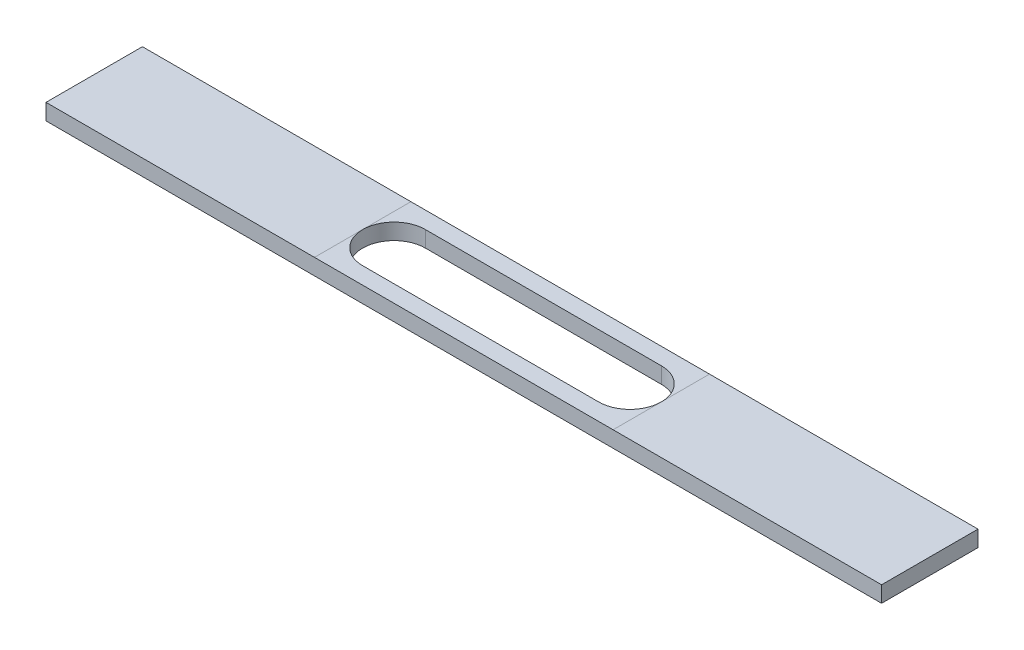
SolidWorks part; units mm, degrees
material "Acrylic (Medium-high impact)"
ref_plane "Front Plane" through (0, 0, 0) normal (0, 0, 1) x (1, 0, 0)
ref_plane "Top Plane" through (0, 0, 0) normal (0, 1, 0) x (1, 0, 0)
ref_plane "Right Plane" through (0, 0, 0) normal (1, 0, 0) x (0, 0, -1)
sketch "Sketch1" plane through (0, 0, 0) normal (0, 1, 0) x (1, 0, 0)
  line L1 (82.55, -9.525) -> (-82.55, -9.525)
  line L2 (82.55, -9.525) -> (82.55, 9.525)
  line L3 (82.55, 9.525) -> (-82.55, 9.525)
  line L4 (-82.55, -9.525) -> (-82.55, 9.525)
  line L5 (82.55, -9.525) -> (-82.55, 9.525) construction
  line L6 (82.55, 9.525) -> (-82.55, -9.525) construction
  point P0 (0, 0)
  dimension "D1" = 19.05
  dimension "D2" = 165.1
extrude "Boss-Extrude1" add sketch "Sketch1" along normal blind 3.175 contours L3 L4 L1 L2
sketch "Sketch3" plane through (0, 3.175, 0) normal (0, 1, 0) x (1, 0, 0)
  line L0 (-29.5, 9.525) -> (-29.5, -9.525)
  line L1 (82.55, 9.525) -> (-82.55, 9.525) construction
  line L2 (82.55, -9.525) -> (-82.55, -9.525) construction
  line L3 (29.5, 9.525) -> (29.5, -9.525)
  line L4 (29.5, 0) -> (-29.5, 0) construction
  point P12 (0, 0)
  dimension "D1" = 59
split line "Split Line1"
sketch "Sketch4" plane through (0, 3.175, 0) normal (0, 1, 0) x (1, 0, 0)
  line L0 (-29.5, -9.525) -> (-29.5, 9.525) construction
  ellipse E0 centre (0, 0) end of major axis (-29.5, 0) minor radius 6.0325
  dimension "D1" = 12.065
extrude "Ellipse" [suppressed] cut sketch "Sketch4" against normal through all
sketch "Sketch5" plane through (0, 3.175, 0) normal (0, 1, 0) x (1, 0, 0)
  line L0 (-23.31, 0) -> (23.31, 0) construction
  line L4 (-23.31, 6.19) -> (23.31, 6.19)
  line L5 (-23.31, -6.19) -> (23.31, -6.19)
  line L6 (29.5, -9.525) -> (29.5, 9.525) construction
  arc A2 (-23.31, 6.19) -> (-23.31, -6.19) centre (-23.31, 0) ccw
  arc A3 (23.31, -6.19) -> (23.31, 6.19) centre (23.31, 0) ccw
  point P2 (0, 0)
  dimension "D1" = 12.38
extrude "Slot" cut sketch "Sketch5" against normal through all
sketch "Sketch6" [suppressed] plane through (0, 3.175, 0) normal (0, 1, 0) x (1, 0, 0)
  line L0 (-24.2316, 7.1289) -> (-19.1516, 7.1289) construction
  line L1 (-24.2316, 8.2973) -> (-19.1516, 8.2973)
  line L2 (-24.2316, 5.9605) -> (-19.1516, 5.9605)
  line L3 (-15.555, 7.1289) -> (-10.475, 7.1289) construction
  line L4 (-15.555, 8.2973) -> (-10.475, 8.2973)
  line L5 (-15.555, 5.9605) -> (-10.475, 5.9605)
  line L6 (-6.8783, 7.1289) -> (-1.7983, 7.1289) construction
  line L7 (-6.8783, 8.2973) -> (-1.7983, 8.2973)
  line L8 (-6.8783, 5.9605) -> (-1.7983, 5.9605)
  line L9 (1.7983, 7.1289) -> (6.8783, 7.1289) construction
  line L10 (1.7983, 8.2973) -> (6.8783, 8.2973)
  line L11 (1.7983, 5.9605) -> (6.8783, 5.9605)
  line L12 (10.475, 7.1289) -> (15.555, 7.1289) construction
  line L13 (10.475, 8.2973) -> (15.555, 8.2973)
  line L14 (10.475, 5.9605) -> (15.555, 5.9605)
  line L15 (19.1516, 7.1289) -> (24.2316, 7.1289) construction
  line L16 (19.1516, 8.2973) -> (24.2316, 8.2973)
  line L17 (19.1516, 5.9605) -> (24.2316, 5.9605)
  line L18 (-15.555, 3.5645) -> (-10.475, 3.5645) construction
  line L19 (-15.555, 4.7329) -> (-10.475, 4.7329)
  line L20 (-15.555, 2.3961) -> (-10.475, 2.3961)
  line L21 (-6.8783, 3.5645) -> (-1.7983, 3.5645) construction
  line L22 (-6.8783, 4.7329) -> (-1.7983, 4.7329)
  line L23 (-6.8783, 2.3961) -> (-1.7983, 2.3961)
  line L24 (1.7983, 3.5645) -> (6.8783, 3.5645) construction
  line L25 (1.7983, 4.7329) -> (6.8783, 4.7329)
  line L26 (1.7983, 2.3961) -> (6.8783, 2.3961)
  line L27 (10.475, 3.5645) -> (15.555, 3.5645) construction
  line L28 (10.475, 4.7329) -> (15.555, 4.7329)
  line L29 (10.475, 2.3961) -> (15.555, 2.3961)
  line L30 (19.1516, 3.5645) -> (24.2316, 3.5645) construction
  line L31 (19.1516, 4.7329) -> (24.2316, 4.7329)
  line L32 (19.1516, 2.3961) -> (24.2316, 2.3961)
  line L33 (-15.555, 0) -> (-10.475, 0) construction
  line L34 (-15.555, 1.1684) -> (-10.475, 1.1684)
  line L35 (-15.555, -1.1684) -> (-10.475, -1.1684)
  line L36 (-6.8783, 0) -> (-1.7983, 0) construction
  line L37 (-6.8783, 1.1684) -> (-1.7983, 1.1684)
  line L38 (-6.8783, -1.1684) -> (-1.7983, -1.1684)
  line L39 (1.7983, 0) -> (6.8783, 0) construction
  line L40 (1.7983, 1.1684) -> (6.8783, 1.1684)
  line L41 (1.7983, -1.1684) -> (6.8783, -1.1684)
  line L42 (10.475, 0) -> (15.555, 0) construction
  line L43 (10.475, 1.1684) -> (15.555, 1.1684)
  line L44 (10.475, -1.1684) -> (15.555, -1.1684)
  line L45 (19.1516, 0) -> (24.2316, 0) construction
  line L46 (19.1516, 1.1684) -> (24.2316, 1.1684)
  line L47 (19.1516, -1.1684) -> (24.2316, -1.1684)
  line L48 (-15.555, -3.5645) -> (-10.475, -3.5645) construction
  line L49 (-15.555, -2.3961) -> (-10.475, -2.3961)
  line L50 (-15.555, -4.7329) -> (-10.475, -4.7329)
  line L51 (-6.8783, -3.5645) -> (-1.7983, -3.5645) construction
  line L52 (-6.8783, -2.3961) -> (-1.7983, -2.3961)
  line L53 (-6.8783, -4.7329) -> (-1.7983, -4.7329)
  line L54 (1.7983, -3.5645) -> (6.8783, -3.5645) construction
  line L55 (1.7983, -2.3961) -> (6.8783, -2.3961)
  line L56 (1.7983, -4.7329) -> (6.8783, -4.7329)
  line L57 (10.475, -3.5645) -> (15.555, -3.5645) construction
  line L58 (10.475, -2.3961) -> (15.555, -2.3961)
  line L59 (10.475, -4.7329) -> (15.555, -4.7329)
  line L60 (19.1516, -3.5645) -> (24.2316, -3.5645) construction
  line L61 (19.1516, -2.3961) -> (24.2316, -2.3961)
  line L62 (19.1516, -4.7329) -> (24.2316, -4.7329)
  line L63 (-15.555, -7.1289) -> (-10.475, -7.1289) construction
  line L64 (-15.555, -5.9605) -> (-10.475, -5.9605)
  line L65 (-15.555, -8.2973) -> (-10.475, -8.2973)
  line L66 (-6.8783, -7.1289) -> (-1.7983, -7.1289) construction
  line L67 (-6.8783, -5.9605) -> (-1.7983, -5.9605)
  line L68 (-6.8783, -8.2973) -> (-1.7983, -8.2973)
  line L69 (1.7983, -7.1289) -> (6.8783, -7.1289) construction
  line L70 (1.7983, -5.9605) -> (6.8783, -5.9605)
  line L71 (1.7983, -8.2973) -> (6.8783, -8.2973)
  line L72 (10.475, -7.1289) -> (15.555, -7.1289) construction
  line L73 (10.475, -5.9605) -> (15.555, -5.9605)
  line L74 (10.475, -8.2973) -> (15.555, -8.2973)
  line L75 (19.1516, -7.1289) -> (24.2316, -7.1289) construction
  line L76 (19.1516, -5.9605) -> (24.2316, -5.9605)
  line L77 (19.1516, -8.2973) -> (24.2316, -8.2973)
  line L78 (-24.2316, 3.5645) -> (-19.1516, 3.5645) construction
  line L79 (-24.2316, 4.7329) -> (-19.1516, 4.7329)
  line L80 (-24.2316, 2.3961) -> (-19.1516, 2.3961)
  line L81 (-24.2316, 0) -> (-19.1516, 0) construction
  line L82 (-24.2316, 1.1684) -> (-19.1516, 1.1684)
  line L83 (-24.2316, -1.1684) -> (-19.1516, -1.1684)
  line L84 (-24.2316, -3.5645) -> (-19.1516, -3.5645) construction
  line L85 (-24.2316, -2.3961) -> (-19.1516, -2.3961)
  line L86 (-24.2316, -4.7329) -> (-19.1516, -4.7329)
  line L87 (-24.2316, -7.1289) -> (-19.1516, -7.1289) construction
  line L88 (-24.2316, -5.9605) -> (-19.1516, -5.9605)
  line L89 (-24.2316, -8.2973) -> (-19.1516, -8.2973)
  line L90 (-25.4, -9.525) -> (-25.4, 9.525) construction
  line L92 (25.4, -9.525) -> (25.4, 9.525) construction
  line L93 (-24.2316, 8.2973) -> (-24.2316, 9.525) construction
  line L94 (25.4, 9.525) -> (-25.4, 9.525) construction
  line L95 (-24.2316, -8.2973) -> (-24.2316, -9.525) construction
  line L96 (25.4, -9.525) -> (-25.4, -9.525) construction
  line L97 (-24.2316, -5.9605) -> (-24.2316, -4.7329) construction
  arc A0 (-24.2316, 8.2973) -> (-24.2316, 5.9605) centre (-24.2316, 7.1289) ccw
  arc A1 (-19.1516, 5.9605) -> (-19.1516, 8.2973) centre (-19.1516, 7.1289) ccw
  arc A2 (-15.555, 8.2973) -> (-15.555, 5.9605) centre (-15.555, 7.1289) ccw
  arc A3 (-10.475, 5.9605) -> (-10.475, 8.2973) centre (-10.475, 7.1289) ccw
  arc A4 (-6.8783, 8.2973) -> (-6.8783, 5.9605) centre (-6.8783, 7.1289) ccw
  arc A5 (-1.7983, 5.9605) -> (-1.7983, 8.2973) centre (-1.7983, 7.1289) ccw
  arc A6 (1.7983, 8.2973) -> (1.7983, 5.9605) centre (1.7983, 7.1289) ccw
  arc A7 (6.8783, 5.9605) -> (6.8783, 8.2973) centre (6.8783, 7.1289) ccw
  arc A8 (10.475, 8.2973) -> (10.475, 5.9605) centre (10.475, 7.1289) ccw
  arc A9 (15.555, 5.9605) -> (15.555, 8.2973) centre (15.555, 7.1289) ccw
  arc A10 (19.1516, 8.2973) -> (19.1516, 5.9605) centre (19.1516, 7.1289) ccw
  arc A11 (24.2316, 5.9605) -> (24.2316, 8.2973) centre (24.2316, 7.1289) ccw
  arc A12 (-15.555, 4.7329) -> (-15.555, 2.3961) centre (-15.555, 3.5645) ccw
  arc A13 (-10.475, 2.3961) -> (-10.475, 4.7329) centre (-10.475, 3.5645) ccw
  arc A14 (-6.8783, 4.7329) -> (-6.8783, 2.3961) centre (-6.8783, 3.5645) ccw
  arc A15 (-1.7983, 2.3961) -> (-1.7983, 4.7329) centre (-1.7983, 3.5645) ccw
  arc A16 (1.7983, 4.7329) -> (1.7983, 2.3961) centre (1.7983, 3.5645) ccw
  arc A17 (6.8783, 2.3961) -> (6.8783, 4.7329) centre (6.8783, 3.5645) ccw
  arc A18 (10.475, 4.7329) -> (10.475, 2.3961) centre (10.475, 3.5645) ccw
  arc A19 (15.555, 2.3961) -> (15.555, 4.7329) centre (15.555, 3.5645) ccw
  arc A20 (19.1516, 4.7329) -> (19.1516, 2.3961) centre (19.1516, 3.5645) ccw
  arc A21 (24.2316, 2.3961) -> (24.2316, 4.7329) centre (24.2316, 3.5645) ccw
  arc A22 (-15.555, 1.1684) -> (-15.555, -1.1684) centre (-15.555, 0) ccw
  arc A23 (-10.475, -1.1684) -> (-10.475, 1.1684) centre (-10.475, 0) ccw
  arc A24 (-6.8783, 1.1684) -> (-6.8783, -1.1684) centre (-6.8783, 0) ccw
  arc A25 (-1.7983, -1.1684) -> (-1.7983, 1.1684) centre (-1.7983, 0) ccw
  arc A26 (1.7983, 1.1684) -> (1.7983, -1.1684) centre (1.7983, 0) ccw
  arc A27 (6.8783, -1.1684) -> (6.8783, 1.1684) centre (6.8783, 0) ccw
  arc A28 (10.475, 1.1684) -> (10.475, -1.1684) centre (10.475, 0) ccw
  arc A29 (15.555, -1.1684) -> (15.555, 1.1684) centre (15.555, 0) ccw
  arc A30 (19.1516, 1.1684) -> (19.1516, -1.1684) centre (19.1516, 0) ccw
  arc A31 (24.2316, -1.1684) -> (24.2316, 1.1684) centre (24.2316, 0) ccw
  arc A32 (-15.555, -2.3961) -> (-15.555, -4.7329) centre (-15.555, -3.5645) ccw
  arc A33 (-10.475, -4.7329) -> (-10.475, -2.3961) centre (-10.475, -3.5645) ccw
  arc A34 (-6.8783, -2.3961) -> (-6.8783, -4.7329) centre (-6.8783, -3.5645) ccw
  arc A35 (-1.7983, -4.7329) -> (-1.7983, -2.3961) centre (-1.7983, -3.5645) ccw
  arc A36 (1.7983, -2.3961) -> (1.7983, -4.7329) centre (1.7983, -3.5645) ccw
  arc A37 (6.8783, -4.7329) -> (6.8783, -2.3961) centre (6.8783, -3.5645) ccw
  arc A38 (10.475, -2.3961) -> (10.475, -4.7329) centre (10.475, -3.5645) ccw
  arc A39 (15.555, -4.7329) -> (15.555, -2.3961) centre (15.555, -3.5645) ccw
  arc A40 (19.1516, -2.3961) -> (19.1516, -4.7329) centre (19.1516, -3.5645) ccw
  arc A41 (24.2316, -4.7329) -> (24.2316, -2.3961) centre (24.2316, -3.5645) ccw
  arc A42 (-15.555, -5.9605) -> (-15.555, -8.2973) centre (-15.555, -7.1289) ccw
  arc A43 (-10.475, -8.2973) -> (-10.475, -5.9605) centre (-10.475, -7.1289) ccw
  arc A44 (-6.8783, -5.9605) -> (-6.8783, -8.2973) centre (-6.8783, -7.1289) ccw
  arc A45 (-1.7983, -8.2973) -> (-1.7983, -5.9605) centre (-1.7983, -7.1289) ccw
  arc A46 (1.7983, -5.9605) -> (1.7983, -8.2973) centre (1.7983, -7.1289) ccw
  arc A47 (6.8783, -8.2973) -> (6.8783, -5.9605) centre (6.8783, -7.1289) ccw
  arc A48 (10.475, -5.9605) -> (10.475, -8.2973) centre (10.475, -7.1289) ccw
  arc A49 (15.555, -8.2973) -> (15.555, -5.9605) centre (15.555, -7.1289) ccw
  arc A50 (19.1516, -5.9605) -> (19.1516, -8.2973) centre (19.1516, -7.1289) ccw
  arc A51 (24.2316, -8.2973) -> (24.2316, -5.9605) centre (24.2316, -7.1289) ccw
  arc A52 (-24.2316, 4.7329) -> (-24.2316, 2.3961) centre (-24.2316, 3.5645) ccw
  arc A53 (-19.1516, 2.3961) -> (-19.1516, 4.7329) centre (-19.1516, 3.5645) ccw
  arc A54 (-24.2316, 1.1684) -> (-24.2316, -1.1684) centre (-24.2316, 0) ccw
  arc A55 (-19.1516, -1.1684) -> (-19.1516, 1.1684) centre (-19.1516, 0) ccw
  arc A56 (-24.2316, -2.3961) -> (-24.2316, -4.7329) centre (-24.2316, -3.5645) ccw
  arc A57 (-19.1516, -4.7329) -> (-19.1516, -2.3961) centre (-19.1516, -3.5645) ccw
  arc A58 (-24.2316, -5.9605) -> (-24.2316, -8.2973) centre (-24.2316, -7.1289) ccw
  arc A59 (-19.1516, -8.2973) -> (-19.1516, -5.9605) centre (-19.1516, -7.1289) ccw
  point P2 (-21.6916, 7.1289)
  point P11 (-13.015, 7.1289)
  point P18 (-4.3383, 7.1289)
  point P25 (4.3383, 7.1289)
  point P32 (13.015, 7.1289)
  point P39 (21.6916, 7.1289)
  point P46 (-13.015, 3.5645)
  point P53 (-4.3383, 3.5645)
  point P60 (4.3383, 3.5645)
  point P67 (13.015, 3.5645)
  point P74 (21.6916, 3.5645)
  point P81 (-13.015, 0)
  point P88 (-4.3383, 0)
  point P95 (4.3383, 0)
  point P102 (13.015, 0)
  point P109 (21.6916, 0)
  point P116 (-13.015, -3.5645)
  point P123 (-4.3383, -3.5645)
  point P130 (4.3383, -3.5645)
  point P137 (13.015, -3.5645)
  point P144 (21.6916, -3.5645)
  point P151 (-13.015, -7.1289)
  point P158 (-4.3383, -7.1289)
  point P165 (4.3383, -7.1289)
  point P172 (13.015, -7.1289)
  point P179 (21.6916, -7.1289)
  point P186 (-21.6916, 3.5645)
  point P193 (-21.6916, 0)
  point P200 (-21.6916, -3.5645)
  point P207 (-21.6916, -7.1289)
  point P217 (-25.4, 0)
  dimension "D4" = 1.1684
  dimension "D3" = 5.08
  dimension "D1" = 6
  dimension "D2" = 5
extrude "Slots" [suppressed] cut sketch "Sketch6" against normal through all
sketch "Sketch7" [suppressed] plane through (0, 3.175, 0) normal (0, 1, 0) x (1, 0, 0)
  line L1 (25.4, 9.525) -> (-25.4, 9.525) construction
  line L8 (7.366, 0) -> (0, 7.366)
  line L9 (7.366, 0) -> (0, -7.366)
  line L10 (0, 7.366) -> (-7.366, 0)
  line L11 (0, -7.366) -> (-7.366, 0)
  line L12 (7.366, 0) -> (-7.366, 0) construction
  line L13 (0, 7.366) -> (0, -7.366) construction
  line L14 (-10.668, 0) -> (-18.034, 7.366)
  line L15 (-10.668, 0) -> (-18.034, -7.366)
  line L16 (-18.034, 7.366) -> (-25.4, 0)
  line L17 (-18.034, -7.366) -> (-25.4, 0)
  line L18 (-10.668, 0) -> (-25.4, 0) construction
  line L19 (-18.034, 7.366) -> (-18.034, -7.366) construction
  line L20 (-25.4, -9.525) -> (-25.4, 9.525) construction
  line L21 (-14.9807, 7.366) -> (-9.017, 1.4023)
  line L22 (-25.4, 3.0533) -> (-25.4, 7.366)
  line L23 (-10.668, 0) -> (-7.366, 0) construction
  line L24 (-9.017, 1.4023) -> (-3.0533, 7.366)
  line L25 (-3.0533, 7.366) -> (-14.9807, 7.366)
  line L26 (-10.668, 0) -> (-9.017, 1.4023) construction
  line L27 (-7.366, 0) -> (-9.017, 1.4023) construction
  line L28 (-25.4, 3.0533) -> (-21.0873, 7.366)
  line L29 (-21.0873, 7.366) -> (-25.4, 7.366)
  line L30 (-21.0873, 7.366) -> (-18.034, 7.366) construction
  line L31 (-14.9807, 7.366) -> (-18.034, 7.366) construction
  line L32 (-3.0533, -7.366) -> (-14.9807, -7.366)
  line L33 (-9.017, -1.4023) -> (-3.0533, -7.366)
  line L34 (-14.9807, -7.366) -> (-9.017, -1.4023)
  line L35 (-25.4, -3.0533) -> (-25.4, -7.366)
  line L36 (-21.0873, -7.366) -> (-25.4, -7.366)
  line L37 (-25.4, -3.0533) -> (-21.0873, -7.366)
  line L38 (14.9807, 7.366) -> (18.034, 7.366) construction
  line L39 (21.0873, 7.366) -> (18.034, 7.366) construction
  line L40 (7.366, 0) -> (9.017, 1.4023) construction
  line L41 (10.668, 0) -> (9.017, 1.4023) construction
  line L42 (10.668, 0) -> (7.366, 0) construction
  line L43 (18.034, 7.366) -> (18.034, -7.366) construction
  line L44 (10.668, 0) -> (25.4, 0) construction
  line L45 (25.4, -3.0533) -> (21.0873, -7.366)
  line L46 (21.0873, -7.366) -> (25.4, -7.366)
  line L47 (25.4, -3.0533) -> (25.4, -7.366)
  line L48 (14.9807, -7.366) -> (9.017, -1.4023)
  line L49 (9.017, -1.4023) -> (3.0533, -7.366)
  line L50 (3.0533, -7.366) -> (14.9807, -7.366)
  line L51 (21.0873, 7.366) -> (25.4, 7.366)
  line L52 (25.4, 3.0533) -> (21.0873, 7.366)
  line L53 (3.0533, 7.366) -> (14.9807, 7.366)
  line L54 (9.017, 1.4023) -> (3.0533, 7.366)
  line L55 (25.4, 3.0533) -> (25.4, 7.366)
  line L56 (14.9807, 7.366) -> (9.017, 1.4023)
  line L57 (18.034, -7.366) -> (25.4, 0)
  line L58 (18.034, 7.366) -> (25.4, 0)
  line L59 (10.668, 0) -> (18.034, -7.366)
  line L60 (10.668, 0) -> (18.034, 7.366)
  point P1 (-18.034, 0)
  point P8 (0, 0)
  point P43 (18.034, 0)
  dimension "D1" = 2.159
  dimension "D2" = 2.159
extrude "Hash" [suppressed] cut sketch "Sketch7" against normal through all
fillet "Fillet2" [suppressed] radius 1.016
sketch "Sketch8" [suppressed] plane through (0, 3.175, 0) normal (0, 1, 0) x (1, 0, 0)
  line L0 (25.4, 0) -> (-25.4, 0) construction
  line L1 (25.4, -4.826) -> (-25.4, -4.826)
  line L2 (25.4, -4.826) -> (25.4, 4.826)
  line L3 (25.4, 4.826) -> (-25.4, 4.826)
  line L4 (-25.4, -4.826) -> (-25.4, 4.826)
  line L5 (25.4, -4.826) -> (-25.4, 4.826) construction
  line L6 (25.4, 4.826) -> (-25.4, -4.826) construction
  line L7 (-25.4, -9.525) -> (-25.4, 9.525) construction
  point P0 (0, 0)
  dimension "D1" = 9.652
extrude "Rectangle" [suppressed] cut sketch "Sketch8" against normal through all
fillet "Fillet3" [suppressed] radius 2.54
equation "\"D2@Sketch7\"=\"D1@Sketch7\""
